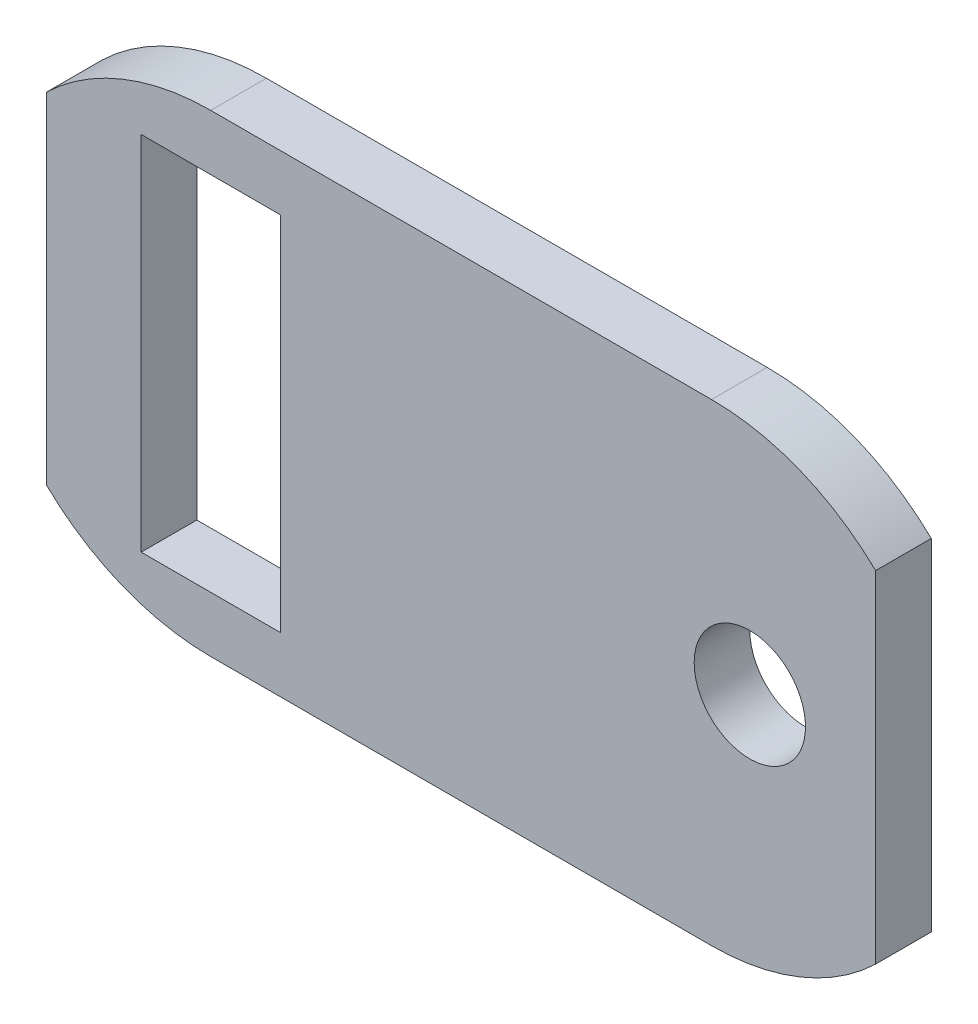
SolidWorks part; units mm, degrees
ref_plane "Front Plane" through (0, 0, 0) normal (0, 0, 1) x (1, 0, 0)
ref_plane "Top Plane" through (0, 0, 0) normal (0, 1, 0) x (1, 0, 0)
ref_plane "Right Plane" through (0, 0, 0) normal (1, 0, 0) x (0, 0, -1)
sketch "Sketch1" plane through (0, 0, 0) normal (0, 0, 1) x (1, 0, 0)
  line L0 (-80.7981, 3.1503) -> (-80.7981, -58.0884)
  line L1 (-51.3243, 15.0309) -> (38.6757, 15.0309)
  line L2 (38.6757, 15.0309) -> (38.6757, -69.9691) construction
  line L3 (38.6757, -69.9691) -> (-51.3243, -69.9691)
  line L4 (68.1496, 3.1503) -> (68.1496, -58.0884)
  arc A0 (-51.3243, 15.0309) -> (-80.7981, 3.1503) centre (-51.3243, -27.4691) ccw
  arc A2 (38.6757, 15.0309) -> (68.1496, 3.1503) centre (38.6757, -27.4691) cw
  arc A3 (-80.7981, -58.0884) -> (-51.3243, -69.9691) centre (-51.3243, -27.4691) ccw
  arc A4 (68.1496, -58.0884) -> (38.6757, -69.9691) centre (38.6757, -27.4691) cw
extrude "Boss-Extrude1" add sketch "Sketch1" along normal blind 10
sketch "Sketch2" plane through (0, 0, 0) normal (0, 0, -1) x (-1, 0, 0)
  line L0 (51.3243, 15.0309) -> (51.3243, 5.0309) construction
  line L1 (51.3243, -69.9691) -> (51.3243, -59.9691) construction
  line L6 (51.3243, 5.0309) -> (51.3243, -59.9691) construction
  line L8 (38.8243, -59.9691) -> (63.8243, -59.9691)
  line L9 (38.8243, -59.9691) -> (38.8243, 5.0309)
  line L10 (38.8243, 5.0309) -> (63.8243, 5.0309)
  line L11 (63.8243, -59.9691) -> (63.8243, 5.0309)
  line L12 (38.8243, -59.9691) -> (63.8243, 5.0309) construction
  line L13 (38.8243, 5.0309) -> (63.8243, -59.9691) construction
  point P7 (51.3243, -27.4691)
extrude "Cut-Extrude2" cut sketch "Sketch2" against normal blind 20
sketch "Sketch3" plane through (0, 0, 0) normal (0, 0, -1) x (-1, 0, 0)
  circle A0 centre (-45.544, -27.4691) radius 10
  point P8 (-54.2177, -27.4691)
  point P9 (-36.2507, -27.4691)
  point P10 (-45.544, -27.4691)
extrude "Cut-Extrude3" cut sketch "Sketch3" against normal blind 20
